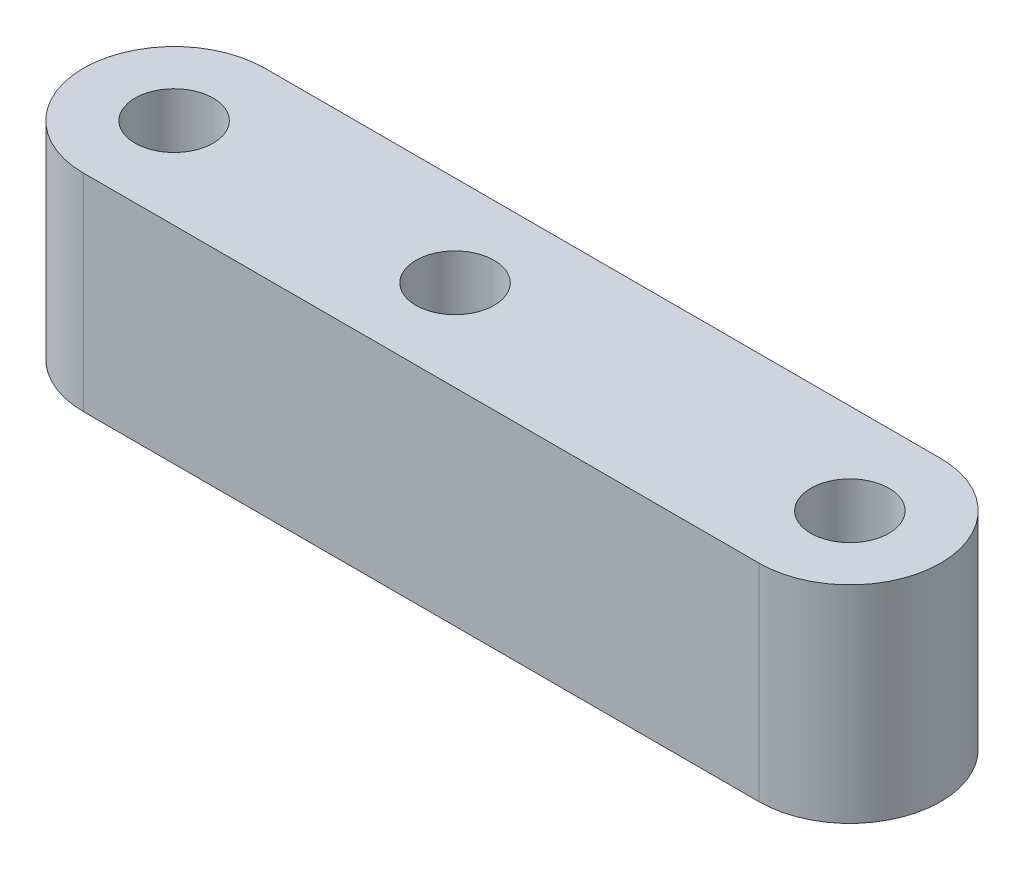
SolidWorks part; units mm, degrees
ref_plane "Front Plane" through (0, 0, 0) normal (0, 0, 1) x (1, 0, 0)
ref_plane "Top Plane" through (0, 0, 0) normal (0, 1, 0) x (1, 0, 0)
ref_plane "Right Plane" through (0, 0, 0) normal (1, 0, 0) x (0, 0, -1)
sketch "Sketch1" plane through (0, 0, 0) normal (0, 1, 0) x (1, 0, 0)
  line L0 (0, 0) -> (61.468, 0) construction
  line L1 (0, 8.255) -> (61.468, 8.255)
  line L2 (0, -8.255) -> (61.468, -8.255)
  circle A0 centre (0, 0) radius 3.556
  circle A2 centre (25.5524, 0) radius 3.556
  circle A3 centre (61.468, 0) radius 3.556
  arc A4 (0, 8.255) -> (0, -8.255) centre (0, 0) ccw
  arc A5 (61.468, -8.255) -> (61.468, 8.255) centre (61.468, 0) ccw
  point P3 (30.734, 0)
  dimension "D1" = 25.5524
  dimension "D2" = 7.112
  dimension "D4" = 8.255
  dimension "D3" = 35.9156
extrude "Boss-Extrude1" add sketch "Sketch1" along normal mid plane 18.796
